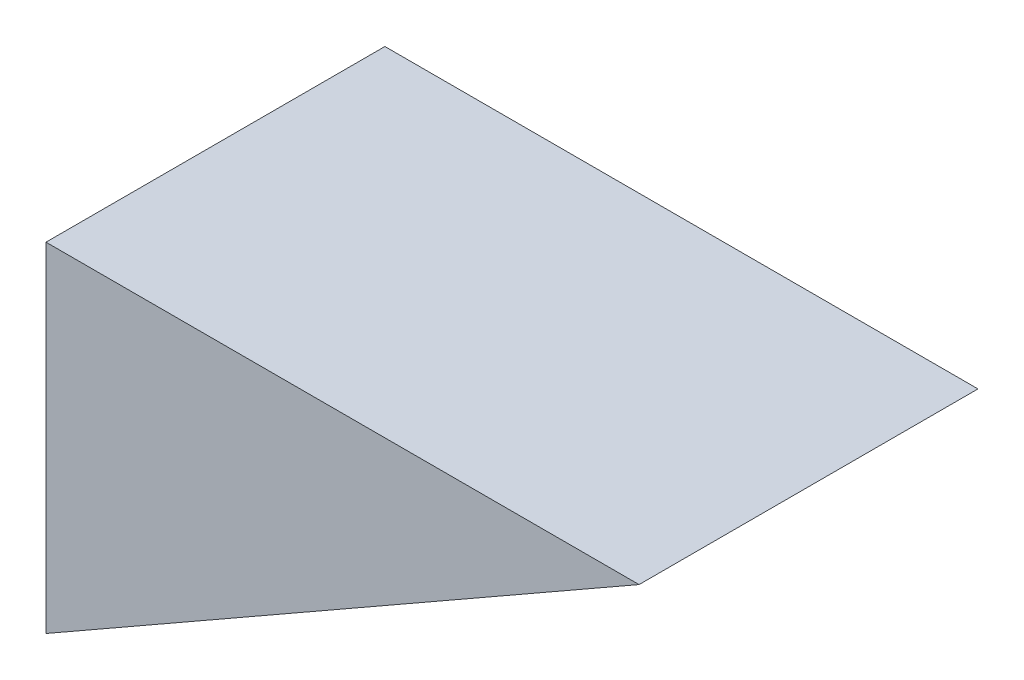
SolidWorks part; units mm, degrees
ref_plane "Front Plane" through (0, 0, 0) normal (0, 0, 1) x (1, 0, 0)
ref_plane "Top Plane" through (0, 0, 0) normal (0, 1, 0) x (1, 0, 0)
ref_plane "Right Plane" through (0, 0, 0) normal (1, 0, 0) x (0, 0, -1)
sketch "Sketch1" plane through (0, 0, 0) normal (0, 0, 1) x (1, 0, 0)
  line L0 (0, 0) -> (0, 20)
  line L1 (0, 20) -> (35, 20)
  line L2 (0, 0) -> (35, 20)
  dimension "D1" = 20
  dimension "D2" = 35
extrude "Boss-Extrude1" add sketch "Sketch1" along normal blind 20
sketch "Sketch2" plane through (0, 0, 0) normal (-1, 0, 0) x (0, 0, 1)
  line L0 (0, 0) -> (2.0231, 0)
  line L1 (20, 0) -> (0, 0) construction
  line L2 (2.0231, 0) -> (2.0231, 17.9909)
  line L3 (20, 0) -> (18.0048, 0)
  line L4 (18.0048, 0) -> (18.0048, 17.9909)
  line L5 (18.0048, 17.9909) -> (2.0231, 17.9909)
  line L6 (2.0231, 0) -> (18.0048, 0)
  line M2 (0, 0) -> (20, 0)
extrude "Cut-Extrude1" cut sketch "Sketch2" against normal blind 15 contours L4 L5 L2 M2
sketch "Sketch3" plane through (0, 0, 0) normal (0.4961, -0.8682, 0) x (0.8682, 0.4961, 0)
  line L0 (17.2763, 18.0048) -> (37.2277, 18.0048)
  line L1 (21.9496, 18.0048) -> (8.926, 18.0048) construction
  line L2 (17.2763, 2.0231) -> (17.2763, 18.0048) construction
  line L3 (37.2277, 18.0048) -> (37.2277, 2.0231)
  line L4 (37.2277, 2.0231) -> (17.2763, 2.0231)
